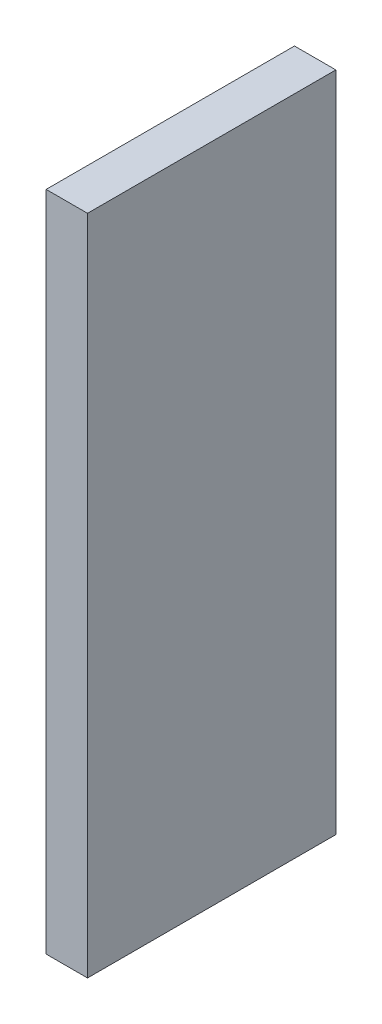
SolidWorks part; units mm, degrees
ref_plane "Front Plane" through (0, 0, 0) normal (0, 0, 1) x (1, 0, 0)
ref_plane "Top Plane" through (0, 0, 0) normal (0, 1, 0) x (1, 0, 0)
ref_plane "Right Plane" through (0, 0, 0) normal (1, 0, 0) x (0, 0, -1)
sketch "Sketch1" plane through (0, 0, 0) normal (1, 0, 0) x (0, 0, -1)
  line L1 (-38.1, -101.6) -> (38.1, -101.6)
  line L2 (-38.1, -101.6) -> (-38.1, 101.6)
  line L3 (-38.1, 101.6) -> (38.1, 101.6)
  line L4 (38.1, -101.6) -> (38.1, 101.6)
  line L5 (-38.1, -101.6) -> (38.1, 101.6) construction
  line L6 (-38.1, 101.6) -> (38.1, -101.6) construction
  point P0 (0, 0)
  dimension "D1" = 76.2
  dimension "D2" = 203.2
extrude "Boss-Extrude1" add sketch "Sketch1" along normal blind 12.7
sketch "Sketch2" plane through (0, 0, 0) normal (1, 0, 0) x (0, 0, -1)
  line L0 (0, -91.44) -> (0, 91.44) construction
  line L1 (0, 91.44) -> (25.4, 91.44) construction
  line L2 (0, 91.44) -> (-25.4, 91.44) construction
  line L3 (-25.4, 91.44) -> (-25.4, -91.44) construction
  line L4 (-25.4, -91.44) -> (25.4, -91.44) construction
  line L5 (25.4, -91.44) -> (25.4, 91.44) construction
  line L6 (-25.4, 0) -> (25.4, 0) construction
  line L7 (-25.4, 66.04) -> (25.4, 66.04)
  line L8 (-25.4, 40.64) -> (25.4, 40.64) construction
  line L9 (-25.4, -66.04) -> (25.4, -66.04) construction
  line L10 (-25.4, -40.64) -> (25.4, -40.64) construction
  line L11 (-8.8832, 91.44) -> (-8.8832, 66.04) construction
  line L12 (-8.8832, 66.04) -> (-8.8832, 40.64) construction
  line L13 (-8.8832, -91.44) -> (-8.8832, -66.04) construction
  line L14 (-8.8832, -66.04) -> (-8.8832, -40.64) construction
  point P4 (0, 0)
  point P12 (0, 0)
  point P15 (0, 66.04)
  point P18 (0, 40.64)
  point P21 (0, -66.04)
  point P24 (0, -40.64)
  dimension "D1" = 25.4
  dimension "D2" = 182.88
